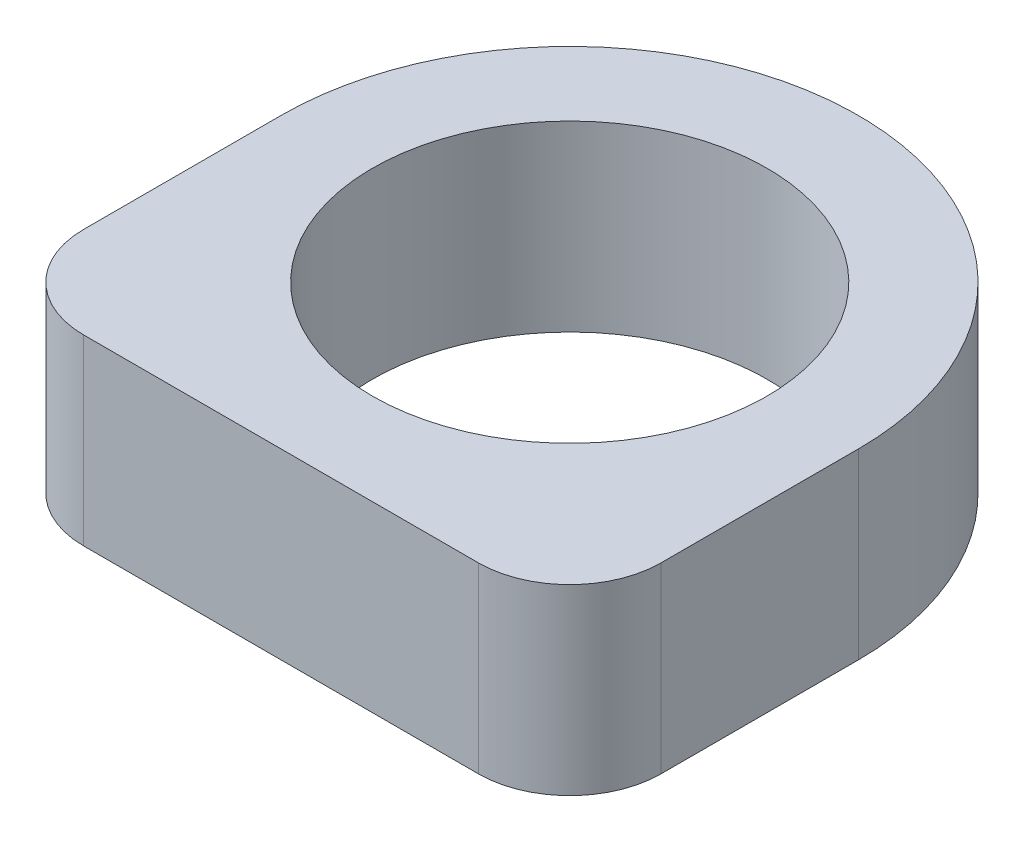
SolidWorks part; units mm, degrees
ref_plane "Front Plane" through (0, 0, 0) normal (0, 0, 1) x (1, 0, 0)
ref_plane "Top Plane" through (0, 0, 0) normal (0, 1, 0) x (1, 0, 0)
ref_plane "Right Plane" through (0, 0, 0) normal (1, 0, 0) x (0, 0, -1)
sketch "Sketch1" plane through (0, 0, 0) normal (0, 1, 0) x (1, 0, 0)
  line L1 (-18.5125, 1.616) -> (13.0875, 1.616)
  line L2 (-18.5125, 1.616) -> (-18.5125, -14.184)
  line L3 (-18.5125, -14.184) -> (13.0875, -14.184)
  line L4 (13.0875, 1.616) -> (13.0875, -14.184)
  circle A0 centre (-2.7125, 1.616) radius 10.8
  circle A1 centre (-2.7125, 1.616) radius 15.8
  dimension "D1" = 21.6
  dimension "D2" = 5
  dimension "D3" = 0
  dimension "D4" = 15.8
  dimension "D5" = 15.8
  dimension "D6" = 15.8
extrude "Boss-Extrude2" add sketch "Sketch1" along normal blind 10 contours A1 L1 A0 | L1 A1 A0 | A1 L3 L4 | A1 L2 L3
fillet "Fillet1" radius 5 2 edges at (-18.5125, 5, 14.184) (13.0875, 5, 14.184)
equation "\"w1\"= ( 21.68 + 21.52 ) / 2"
equation "\"w2\"= ( 19.35 + 19.57 ) / 2"
equation "\"w3\"= 17.03"
equation "\"w4\"= ( 15.09 + 15.18 ) / 2"
equation "\"w5\"= 13.2"
equation "\"w6\"= ( 11.13 + 11.42 ) / 2"
equation "\"w7\"= 9.3"
equation "\"mount_height\" = 20"
equation "\"mount_thickness\"= 5"
equation "\"D1@Sketch1\"=\"w1\""
equation "\"D2@Sketch1\"=\"mount_thickness\""
equation "\"webcam depth\"= 40.4"
equation "\"D6@Sketch1\"=\"D1@Sketch1\"/2+\"D2@Sketch1\""
equation "\"D5@Sketch1\"=\"D6@Sketch1\""
